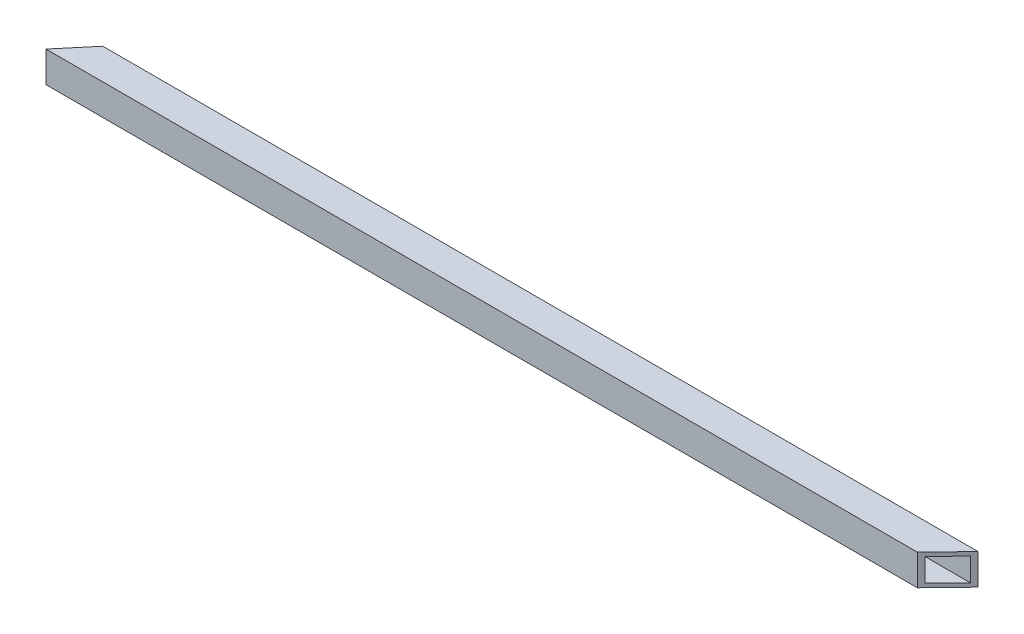
SolidWorks part; units mm, degrees
ref_plane "Front Plane" through (0, 0, 0) normal (0, 0, 1) x (1, 0, 0)
ref_plane "Top Plane" through (0, 0, 0) normal (0, 1, 0) x (1, 0, 0)
ref_plane "Right Plane" through (0, 0, 0) normal (1, 0, 0) x (0, 0, -1)
sketch "Sketch1" plane through (0, 0, 0) normal (1, 0, 0) x (0, 0, -1)
  line L0 (4.7625, 4.7625) -> (-4.7625, 4.7625)
  line L1 (6.35, 6.35) -> (-6.35, 6.35)
  line L2 (6.35, 6.35) -> (6.35, -6.35)
  line L3 (6.35, -6.35) -> (-6.35, -6.35)
  line L4 (-6.35, 6.35) -> (-6.35, -6.35)
  line L5 (6.35, 6.35) -> (-6.35, -6.35) construction
  line L6 (6.35, -6.35) -> (-6.35, 6.35) construction
  line L7 (-4.7625, 4.7625) -> (-4.7625, -4.7625)
  line L8 (4.7625, -4.7625) -> (-4.7625, -4.7625)
  line L9 (4.7625, 4.7625) -> (4.7625, -4.7625)
  dimension "D1" = 12.7
  dimension "D2" = 12.7
  dimension "D3" = 1.5875
extrude "Boss-Extrude1" add sketch "Sketch1" along normal mid plane 370.84
sketch "Sketch2" plane through (0, 0, 0) normal (0, 1, 0) x (1, 0, 0)
  line L0 (-185.42, -6.35) -> (-135.9836, 52.566) construction
  line L1 (-185.42, -6.35) -> (-174.2505, 6.9613)
  line L2 (-185.42, -6.35) -> (-194.2478, 1.0574)
  line L3 (-174.2505, 6.9613) -> (-183.0782, 14.3687)
  line L4 (-194.2478, 1.0574) -> (-183.0782, 14.3687)
extrude "Cut-Extrude1" cut sketch "Sketch2" against normal through all and the other way through all
sketch "Sketch3" plane through (0, 0, 0) normal (0, 1, 0) x (1, 0, 0)
  line L0 (185.42, 6.35) -> (173.1509, -6.35)
  line L2 (173.1509, -6.35) -> (185.42, -6.35)
  line L5 (185.42, -6.35) -> (185.42, 6.35)
extrude "Cut-Extrude2" cut sketch "Sketch3" against normal through all and the other way through all
